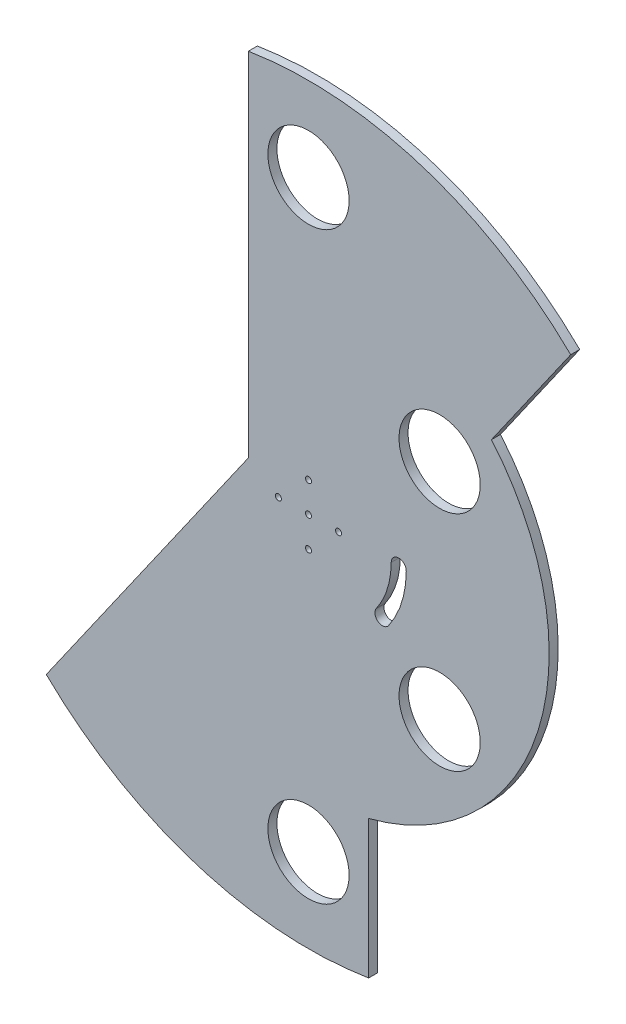
SolidWorks part; units mm, degrees
ref_plane "Front Plane" through (0, 0, 0) normal (0, 0, 1) x (1, 0, 0)
ref_plane "Top Plane" through (0, 0, 0) normal (0, 1, 0) x (1, 0, 0)
ref_plane "Right Plane" through (0, 0, 0) normal (1, 0, 0) x (0, 0, -1)
sketch "Sketch1" plane through (0, 0, 0) normal (0, 0, 1) x (1, 0, 0)
  line L0 (-16.383, 11.4715) -> (-87.1564, -89.6033)
  line L1 (0, -97.082) -> (0, 97.082) construction
  line L2 (43.5926, -37.082) -> (0, 0) construction
  line L3 (43.5926, 37.082) -> (0, 0) construction
  line L4 (20, 0) -> (20, -123.3896) construction
  line L5 (0, 0) -> (-71.6971, -102.394) construction
  line L6 (16.383, -11.4715) -> (87.1564, 89.6033) construction
  line L7 (0, 0) -> (71.6971, 102.394) construction
  line L8 (60.8121, 51.9797) -> (87.1564, 89.6033)
  line L9 (20, -77.4597) -> (20, -123.3896)
  line L10 (-20, 0) -> (-20, 123.3896)
  circle A0 centre (43.5926, -37.082) radius 13.5
  circle A1 centre (43.5926, 37.082) radius 13.5
  circle A2 centre (0, 0) radius 125 construction
  circle A3 centre (0, 0) radius 20 construction
  circle A4 centre (0, 0) radius 80 construction
  arc A5 (20, -77.4597) -> (60.8121, 51.9797) centre (0, 0) ccw
  circle A6 centre (0, -97.082) radius 13.5
  arc A7 (-87.1564, -89.6033) -> (20, -123.3896) centre (0, 0) ccw
  circle A8 centre (0, 97.082) radius 13.5
  arc A9 (-20, 123.3896) -> (87.1564, 89.6033) centre (0, 0) cw
  arc A11 (30, 0) -> (24.5746, -17.2073) centre (0, 0) cw construction
  arc A12 (26.6224, -18.6412) -> (32.5, 0) centre (0, 0) ccw
  arc A13 (22.5267, -15.7734) -> (27.5, 0) centre (0, 0) ccw
  arc A14 (22.5267, -15.7734) -> (26.6224, -18.6412) centre (24.5746, -17.2073) ccw
  arc A15 (32.5, 0) -> (27.5, 0) centre (30, 0) ccw
  point P31 (28.6115, -9.0212)
  dimension "D1" = 250
  dimension "D2" = 35
  dimension "D3" = 40
  dimension "D10" = 30
  dimension "D11" = 5
  dimension "D12" = 27
  dimension "D13" = 35
  dimension "D14" = 160
  dimension "D4" = 194.1641
  dimension "D5" = 57.231
  dimension "D6" = 49.614
  dimension "D7" = 49.614
  dimension "D8" = 35
  dimension "D9" = 49.614
extrude "Boss-Extrude1" add sketch "Sketch1" along normal blind 3
sketch "Sketch2" plane through (0, 0, 3) normal (0, 0, 1) x (1, 0, 0)
  circle A2 centre (0, 0) radius 10 construction
  point P13 (0, 0)
  point P14 (0, -10)
  point P17 (10, 0)
  point P18 (0, 10)
  point P19 (-10, 0)
  dimension "D1" = 20
hole_wizard "Ø2.0mm Dowel Hole1" positions "Sketch3" profile "Sketch4" hole size "Ø2.0" standard "ANSI Metric"
sketch "Sketch3" plane through (0, 0, 3) normal (0, 0, 1) x (1, 0, 0)
  point P0 (0, -10)
  point P3 (10, 0)
  point P6 (0, 10)
  point P9 (0, 0)
  point P12 (-10, 0)
sketch "Sketch4" plane through (0, -10, 3) normal (1, 0, 0) x (0, -1, 0)
  line L0 (0, 0) -> (0, 3.5999)
  line L1 (0, 3.5999) -> (1, 2.999)
  line L2 (1, 2.999) -> (1, 0)
  line L5 (1, 0) -> (0, 0)
  line L10 (0, 3.5999) -> (-1, 2.999) construction
  line L11 (0, -6.35) -> (0, 107.95) construction
  dimension "Hole Dia." = 2
  dimension "Hole Depth" = 2.999
  dimension "Drill Angle" = 118
